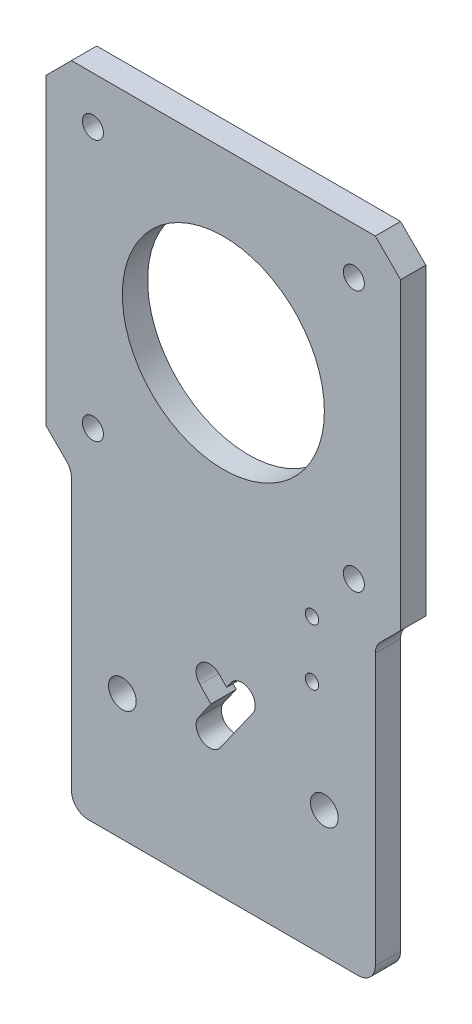
SolidWorks part; units mm, degrees
ref_plane "Plano frontal" through (0, 0, 0) normal (0, 0, 1) x (1, 0, 0)
ref_plane "Plano superior" through (0, 0, 0) normal (0, 1, 0) x (1, 0, 0)
ref_plane "Plano direito" through (0, 0, 0) normal (1, 0, 0) x (0, 0, -1)
sketch "Sketch1" plane through (0, 0, 0) normal (0, 0, 1) x (1, 0, 0)
  line L0 (149.1978, -56.055) -> (-642.8022, -56.055) construction
  line L2 (18.05, -56.055) -> (18.05, -21.05)
  line L4 (-18.05, -56.055) -> (-18.05, -21.05)
  line L5 (18.05, -56.055) -> (-18.05, -56.055)
  line L16 (-21.05, -18.05) -> (-18.05, -21.05)
  line L18 (18.05, -21.05) -> (21.05, -18.05)
  line L19 (21.05, -18.05) -> (21.05, 18.05)
  line L20 (21.05, 18.05) -> (18.05, 21.05)
  line L21 (18.05, 21.05) -> (-18.05, 21.05)
  line L22 (-18.05, 21.05) -> (-21.05, 18.05)
  line L23 (-21.05, 18.05) -> (-21.05, -18.05)
  circle A3 centre (0, 0) radius 12
  dimension "D2" = 36.1
  dimension "D3" = 4.2426
extrude "Boss-Extrude1" add sketch "Sketch1" along normal blind 3
hole_wizard "Tap Drill for M3 Tap1" positions "Sketch3" profile "Sketch2" hole size "M3" standard "ISO"
sketch "Sketch3" plane through (0, 0, 3) normal (0, 0, 1) x (1, 0, 0)
  point P0 (-15.5, 15.5)
  point P3 (15.5, 15.5)
  point P6 (-15.5, -15.5)
  point P9 (15.5, -15.5)
sketch "Sketch2" plane through (-15.5, 15.5, 3) normal (1, 0, 0) x (0, -1, 0)
  line L0 (0, 0) -> (0, 5.7511)
  line L1 (0, 5.7511) -> (1.25, 5)
  line L2 (1.25, 5) -> (1.25, 0)
  line L5 (1.25, 0) -> (0, 0)
  line L10 (0, 5.7511) -> (-1.25, 5) construction
  line L11 (0, -6.35) -> (0, 107.95) construction
  dimension "Hole Dia." = 2.5
  dimension "Hole Depth" = 5
  dimension "Drill Angle" = 118
hole_wizard "Tap Drill for M4 Tap1" positions "Sketch5" profile "Sketch4" hole size "M4" standard "ISO"
sketch "Sketch5" plane through (0, 0, 3) normal (0, 0, 1) x (1, 0, 0)
  line L1 (0, -56.055) -> (0, -21.05) construction
  line L2 (-18.05, -56.055) -> (18.05, -56.055) construction
  line L3 (149.1978, -41.055) -> (-642.8022, -41.055) construction
  point P40 (-12, -41.055)
  point P45 (12, -41.055)
  dimension "D1" = 12
sketch "Sketch4" plane through (12, -41.055, 3) normal (1, 0, 0) x (0, -1, 0)
  line L0 (0, 0) -> (0, 5.9914)
  line L1 (0, 5.9914) -> (1.65, 5)
  line L2 (1.65, 5) -> (1.65, 0)
  line L5 (1.65, 0) -> (0, 0)
  line L10 (0, 5.9914) -> (-1.65, 5) construction
  line L11 (0, -6.35) -> (0, 107.95) construction
  dimension "Hole Dia." = 3.3
  dimension "Hole Depth" = 5
  dimension "Drill Angle" = 118
fillet "Fillet1" radius 2 4 edges at (18.05, -21.05, 1.5) (18.05, -56.055, 1.5) (-18.05, -56.055, 1.5) (-18.05, -21.05, 1.5)
hole_wizard "Tap Drill for M2 Tap1" positions "Sketch7" profile "Sketch6" hole size "M2" standard "ISO"
sketch "Sketch7" plane through (0, 0, 3) normal (0, 0, 1) x (1, 0, 0)
  point P0 (10.5295, -21.8613)
  point P3 (10.5295, -28.5613)
sketch "Sketch6" plane through (10.5295, -21.8613, 3) normal (1, 0, 0) x (0, -1, 0)
  line L0 (0, 0) -> (0, 5.4807)
  line L1 (0, 5.4807) -> (0.8, 5)
  line L2 (0.8, 5) -> (0.8, 0)
  line L5 (0.8, 0) -> (0, 0)
  line L10 (0, 5.4807) -> (-0.8, 5) construction
  line L11 (0, -6.35) -> (0, 107.95) construction
  dimension "Hole Dia." = 1.6
  dimension "Hole Depth" = 5
  dimension "Drill Angle" = 118
sketch "Sketch8" plane through (0, 0, 0) normal (0, 0, 1) x (1, 0, 0)
  line L0 (9.1176, -56.055) -> (-8.1087, -56.055) construction
  line L1 (0.5044, -56.055) -> (0.5044, -38.2118) construction
  line L5 (3.4965, -35.3145) -> (-0.3508, -40.7863)
  line L6 (0.8993, -33.4883) -> (0.385, -34.2197)
  line L8 (-0.5094, -33.2967) -> (0.5044, -34.343)
  line L9 (-2.7895, -35.5061) -> (-1.4741, -36.8637)
  line L10 (-1.4741, -36.8637) -> (-2.9481, -38.9601)
  line L11 (0.5044, -34.343) -> (0.5044, -20.8461) construction
  arc A1 (3.4965, -35.3145) -> (0.8993, -33.4883) centre (2.1979, -34.4014) ccw
  arc A2 (-2.9481, -38.9601) -> (-0.3508, -40.7863) centre (-1.6495, -39.8732) ccw
  arc A3 (-0.5094, -33.2967) -> (-2.7895, -35.5061) centre (-1.6495, -34.4014) ccw
  point P13 (0.2742, -37.1373)
  point P18 (-0.5725, -35.5128)
extrude "Cut-Extrude1" cut sketch "Sketch8" along normal blind 10
